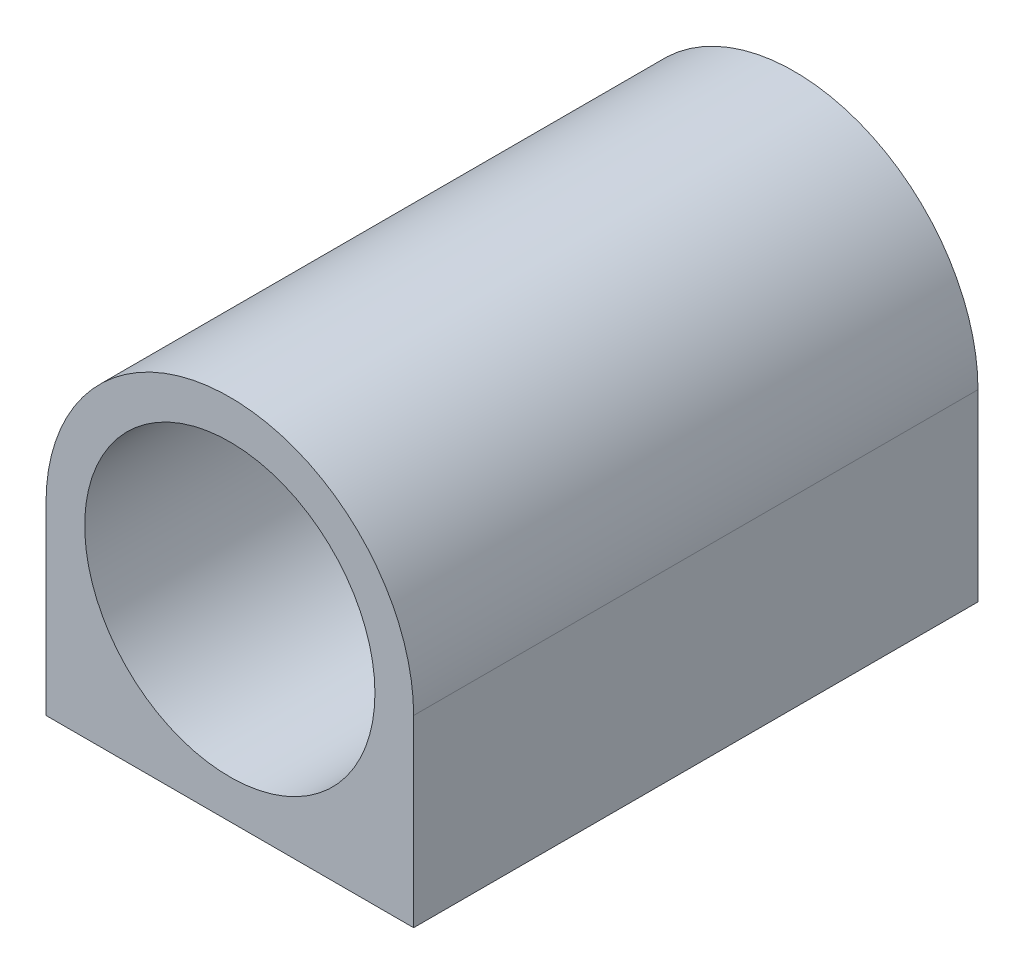
SolidWorks part; units mm, degrees
ref_plane "Front Plane" through (0, 0, 0) normal (0, 0, 1) x (1, 0, 0)
ref_plane "Top Plane" through (0, 0, 0) normal (0, 1, 0) x (1, 0, 0)
ref_plane "Right Plane" through (0, 0, 0) normal (1, 0, 0) x (0, 0, -1)
sketch "Sketch1" plane through (0, 0, 0) normal (0, 0, 1) x (1, 0, 0)
  line L0 (0, 0) -> (22.8, 0)
  line L1 (22.8, 0) -> (22.8, 11.4)
  line L2 (0, 11.4) -> (0, 0)
  arc A0 (22.8, 11.4) -> (0, 11.4) centre (11.4, 11.4) ccw
  circle A1 centre (11.4, 11.4) radius 9
  dimension "D1" = 18
  dimension "D2" = 2.4
  dimension "D3" = 11.4
extrude "Boss-Extrude1" add sketch "Sketch1" along normal blind 35
